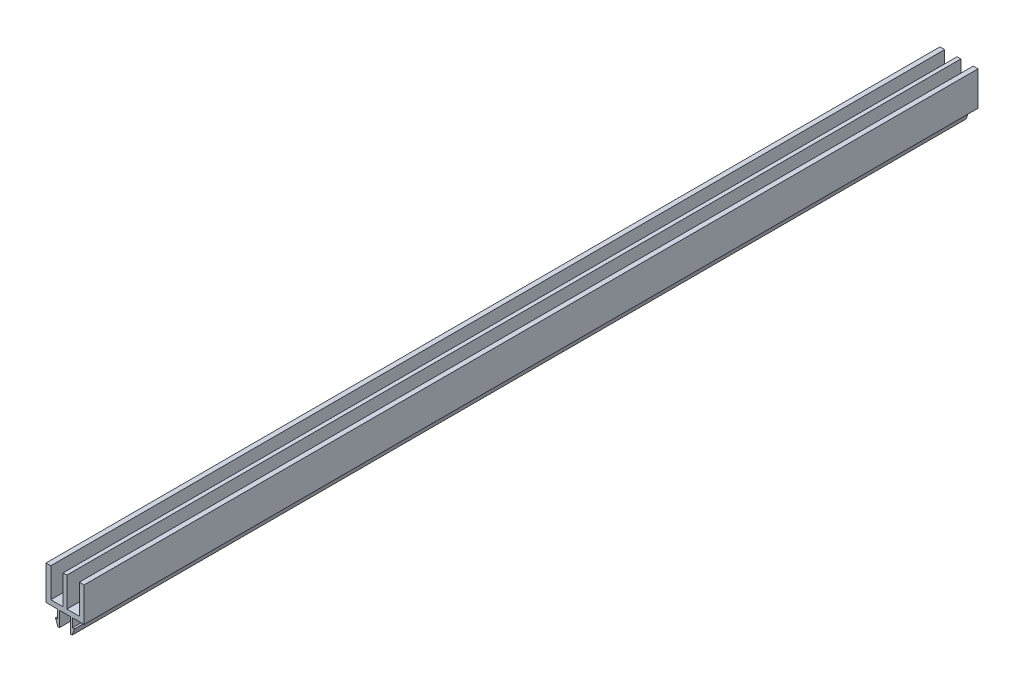
SolidWorks part; units mm, degrees
ref_plane "Plan de face" through (0, 0, 0) normal (0, 0, 1) x (1, 0, 0)
ref_plane "Plan de dessus" through (0, 0, 0) normal (0, 1, 0) x (1, 0, 0)
ref_plane "Plan de droite" through (0, 0, 0) normal (1, 0, 0) x (0, 0, -1)
ref_plane "Plan1" through (0, 0, 50) normal (0, 0, 1) x (1, 0, 0)
sketch "Esquisse1" plane through (0, 0, 50) normal (0, 0, 1) x (1, 0, 0)
  line L0 (-1, 2.5) -> (-7.5, 2.5)
  line L1 (-7.5, 2.5) -> (-7.5, 18)
  line L2 (-7.5, 18) -> (-10, 18)
  line L3 (-10, 18) -> (-10, 0)
  line L4 (-10, 0) -> (-4, 0)
  line L5 (-4, 0) -> (-4, -4.5)
  line L6 (-4, -4.5) -> (-5, -4.5)
  line L7 (-5, -4.5) -> (-3.75, -8)
  line L8 (-3.75, -8) -> (-3, -8)
  line L9 (-3, -8) -> (-3, 0)
  line L10 (-3, 0) -> (3, 0)
  line L11 (3, 0) -> (3, -8)
  line L12 (3, -8) -> (3.75, -8)
  line L13 (3.75, -8) -> (5, -4.5)
  line L14 (5, -4.5) -> (4, -4.5)
  line L15 (4, -4.5) -> (4, 0)
  line L16 (4, 0) -> (10, 0)
  line L17 (10, 0) -> (10, 18)
  line L18 (10, 18) -> (7.5, 18)
  line L19 (7.5, 18) -> (7.5, 2.5)
  line L20 (7.5, 2.5) -> (1, 2.5)
  line L21 (1, 2.5) -> (1, 18)
  line L22 (1, 18) -> (-1, 18)
  line L23 (-1, 18) -> (-1, 2.5)
extrude "Boss.-Extru.1" add sketch "Esquisse1" against normal blind 470
